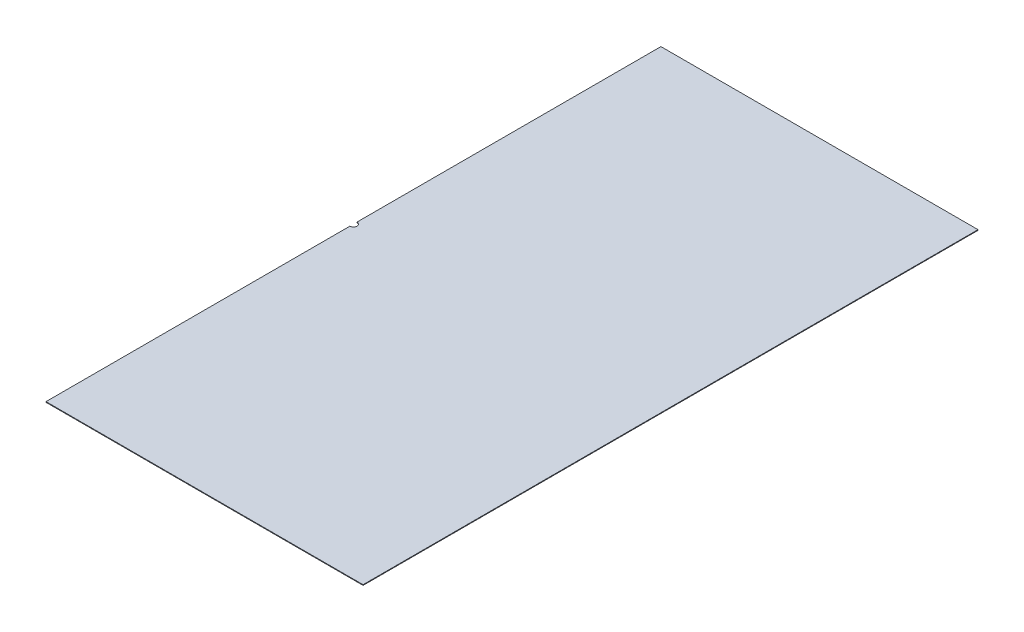
SolidWorks part; units mm, degrees
ref_plane "Front Plane" through (0, 0, 0) normal (0, 0, 1) x (1, 0, 0)
ref_plane "Top Plane" through (0, 0, 0) normal (0, 1, 0) x (1, 0, 0)
ref_plane "Right Plane" through (0, 0, 0) normal (1, 0, 0) x (0, 0, -1)
sketch "Sketch1" plane through (0, 0, 0) normal (0, 1, 0) x (1, 0, 0)
  line L0 (495, -960) -> (495, 960)
  line L1 (495, 960) -> (-495, 960)
  line L3 (495, -960) -> (-495, -960)
  line L4 (-495, 960) -> (-495, 11)
  line L5 (-495, -11) -> (-495, -960)
  arc A0 (-495, -11) -> (-495, 11) centre (-495, 0) ccw
  point P0 (0, 0)
  dimension "D1" = 1920
  dimension "D2" = 990
extrude "Boss-Extrude1" add sketch "Sketch1" along normal blind 2
